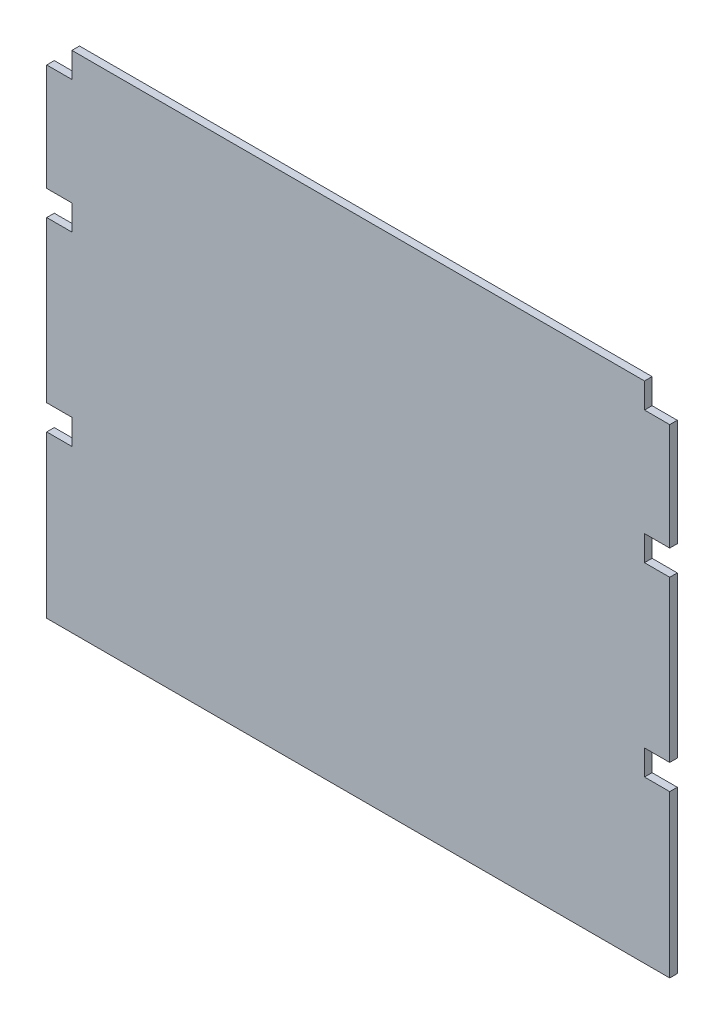
SolidWorks part; units mm, degrees
ref_plane "Plan de face" through (0, 0, 0) normal (0, 0, 1) x (1, 0, 0)
ref_plane "Plan de dessus" through (0, 0, 0) normal (0, 1, 0) x (1, 0, 0)
ref_plane "Plan de droite" through (0, 0, 0) normal (1, 0, 0) x (0, 0, -1)
sketch "Esquisse1" plane through (0, 0, 0) normal (0, 0, 1) x (1, 0, 0)
  line L1 (0, 0) -> (247, 0)
  line L2 (0, 0) -> (0, 200)
  line L3 (0, 200) -> (247, 200)
  line L4 (247, 0) -> (247, 200)
  dimension "D1" = 247
  dimension "D2" = 200
extrude "Boss.-Extru.1" add sketch "Esquisse1" along normal blind 3
sketch "Esquisse2" plane through (0, 0, 3) normal (0, 0, 1) x (1, 0, 0)
  line L0 (247, 0) -> (247, 200) construction
  line L2 (247, 200) -> (237, 200)
  line L4 (247, 200) -> (247, 190)
  line L5 (247, 190) -> (237, 190)
  line L6 (237, 200) -> (237, 190)
  line L7 (247, 147.6) -> (237, 147.6)
  line L8 (247, 147.6) -> (247, 137.6)
  line L9 (247, 137.6) -> (237, 137.6)
  line L10 (237, 147.6) -> (237, 137.6)
  line L11 (123.5, 0) -> (123.5, 249.4021) construction
  line L12 (247, 74) -> (237, 74)
  line L13 (247, 74) -> (247, 64)
  line L14 (247, 64) -> (237, 64)
  line L15 (237, 74) -> (237, 64)
  line L16 (0, 0) -> (247, 0) construction
  line L17 (10, 74) -> (10, 64)
  line L18 (0, 64) -> (10, 64)
  line L19 (0, 74) -> (0, 64)
  line L20 (0, 74) -> (10, 74)
  line L21 (10, 147.6) -> (10, 137.6)
  line L22 (0, 137.6) -> (10, 137.6)
  line L23 (0, 147.6) -> (0, 137.6)
  line L24 (0, 147.6) -> (10, 147.6)
  line L25 (10, 200) -> (10, 190)
  line L26 (0, 190) -> (10, 190)
  line L27 (0, 200) -> (0, 190)
  line L28 (0, 200) -> (10, 200)
  dimension "D1" = 10
  dimension "D2" = 10
  dimension "D3" = 10
  dimension "D4" = 10
  dimension "D5" = 42.4
  dimension "D6" = 10
  dimension "D7" = 10
  dimension "D8" = 63.6
extrude "Enlèv. mat.-Extru.1" cut sketch "Esquisse2" against normal through all
